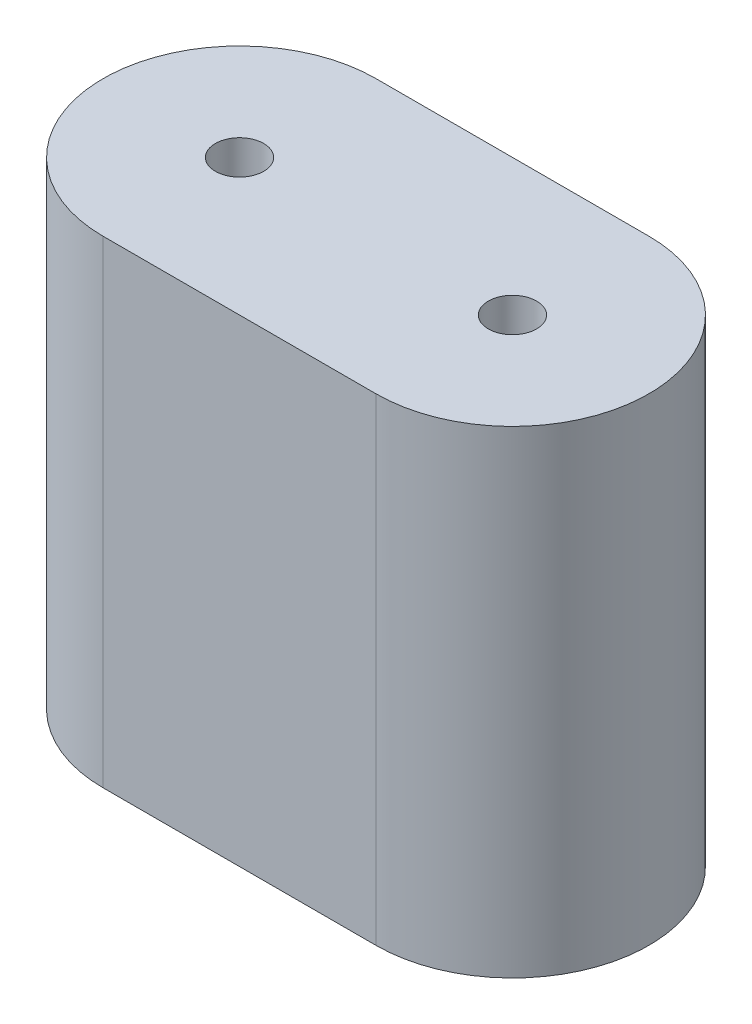
SolidWorks part; units mm, degrees
ref_plane "Front Plane" through (0, 0, 0) normal (0, 0, 1) x (1, 0, 0)
ref_plane "Top Plane" through (0, 0, 0) normal (0, 1, 0) x (1, 0, 0)
ref_plane "Right Plane" through (0, 0, 0) normal (1, 0, 0) x (0, 0, -1)
sketch "Sketch1" plane through (0, 0, 0) normal (0, 1, 0) x (1, 0, 0)
  line L0 (-12.7, 12.7) -> (12.7, 12.7)
  line L1 (12.7, -12.7) -> (-12.7, -12.7)
  arc A0 (-12.7, 12.7) -> (-12.7, -12.7) centre (-12.7, 0) ccw
  arc A1 (12.7, 12.7) -> (12.7, -12.7) centre (12.7, 0) cw
  point P0 (12.7, 0)
  point P1 (-12.7, 0)
  dimension "D3" = 12.7
  dimension "D4" = 12.7
  dimension "D1" = 12.7
  dimension "D2" = 12.7
extrude "Boss-Extrude1" add sketch "Sketch1" along normal blind 44.45
hole_wizard "#8 Clearance Hole1" positions "Sketch2" profile "Sketch3" hole size "#8" standard "ANSI Inch" end condition through all
sketch "Sketch2" plane through (0, 0, 0) normal (0, -1, 0) x (-1, 0, 0)
  point P0 (-12.7, 0)
  point P3 (12.7, 0)
sketch "Sketch3" plane through (12.7, 0, 0) normal (1, 0, 0) x (0, 0, -1)
  line L0 (0, 0) -> (0, 44.45)
  line L1 (0, 44.45) -> (2.2479, 44.45)
  line L2 (2.2479, 44.45) -> (2.2479, 0)
  line L5 (2.2479, 0) -> (0, 0)
  line L11 (0, -6.35) -> (0, 107.95) construction
  dimension "Thru Hole Dia." = 4.4958
  dimension "Thru Hole Depth" = 44.45
